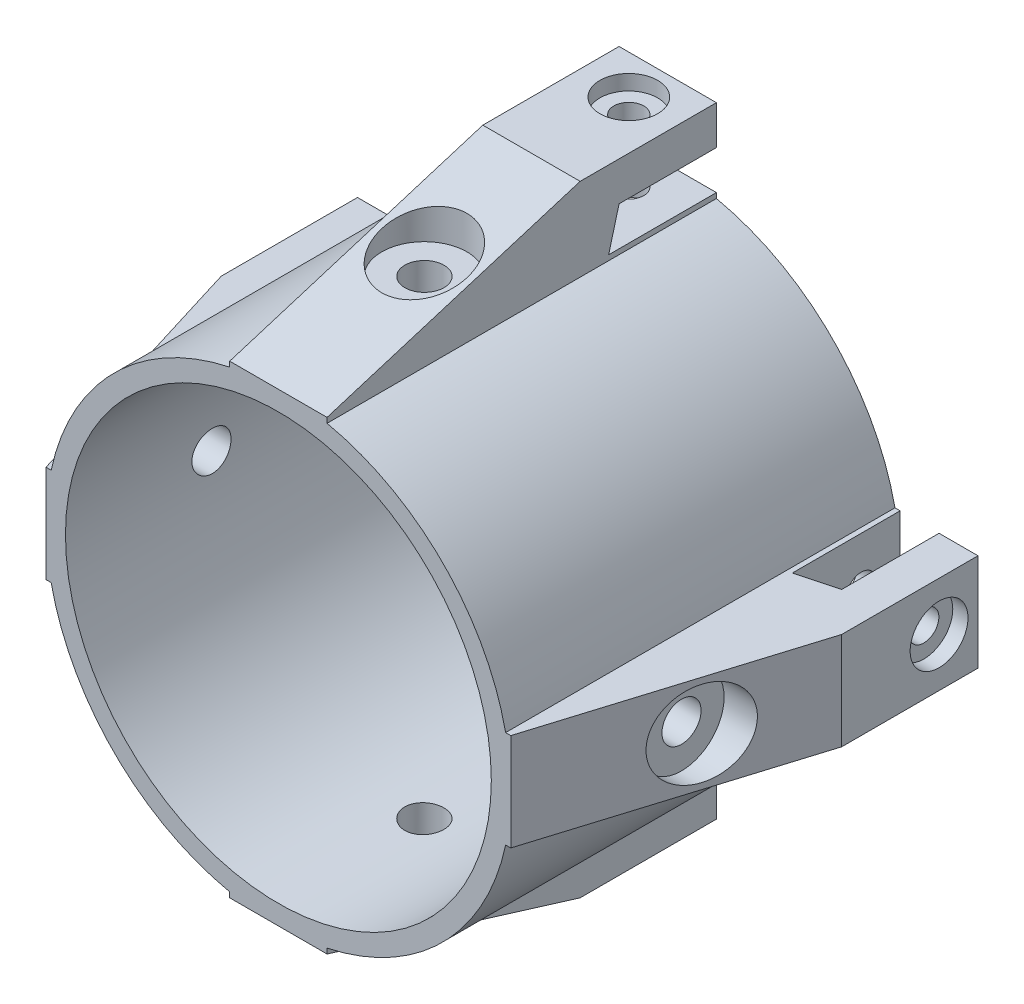
SolidWorks part; units mm, degrees
ref_plane "Front Plane" through (0, 0, 0) normal (1, 0, 0) x (0, 1, 0)
ref_plane "Top Plane" through (0, 0, 0) normal (0, 0, 1) x (0, 1, 0)
ref_plane "Right Plane" through (0, 0, 0) normal (0, 1, 0) x (-1, 0, 0)
sketch "Sketch3" plane through (0, 0, 0) normal (0, 0, 1) x (0, 1, 0)
  circle A0 centre (0, 0) radius 27.7812
  circle A1 centre (0, 0) radius 30.3213
  dimension "D1" = 55.5625
  dimension "D2" = 2.54
extrude "base_ring" add sketch "Sketch3" along normal blind 50.8
sketch "Sketch6" plane through (0, 0, 0) normal (1, 0, 0) x (0, 1, 0)
  line L0 (27.7812, 50.8) -> (27.7812, 0)
  line L1 (-30.3213, 0) -> (30.3213, 0) construction
  line L2 (27.7812, 50.8) -> (30.3213, 50.8)
  line L3 (30.3213, 50.8) -> (40.4813, 17.78)
  line L4 (40.4813, 17.78) -> (40.4813, 0)
  line L5 (40.4813, 0) -> (35.4013, 0)
  line L6 (35.4013, 0) -> (35.4013, 12.7)
  line L7 (35.4013, 12.7) -> (30.3213, 14.0612)
  line L8 (30.3213, 0) -> (30.3213, 50.8) construction
  line L9 (30.3213, 14.0612) -> (30.3213, 0)
  line L10 (30.3213, 0) -> (27.7812, 0)
  point P5 (40.4813, 12.6915)
  dimension "D1" = 75
  dimension "D2" = 5.08
  dimension "D3" = 12.7
  dimension "D4" = 17.78
  dimension "D5" = 5.08
extrude "hook" add sketch "Sketch6" along normal mid plane 12.7
sketch "Sketch7" plane through (0, 40.4813, 0) normal (0, 1, 0) x (-1, 0, 0)
  line L0 (0, 0) -> (0, 5.08) construction
  point P3 (0, 5.08)
  dimension "D2" = 5.08
hole_wizard "CBORE for #5 Binding Head Machine Screw1" positions "Sketch7" profile "Sketch8" counterbore size "#5" standard "ANSI Inch"
sketch "Sketch8" plane through (0, 40.4813, 5.08) normal (1, 0, 0) x (0, 0, 1)
  line L0 (0, 0) -> (0, 39.2752)
  line L1 (0, 39.2752) -> (1.9558, 38.1)
  line L2 (1.9558, 38.1) -> (1.9558, 1.9812)
  line L3 (1.9558, 1.9812) -> (3.7706, 1.9812)
  line L4 (3.7706, 1.9812) -> (3.7706, 0)
  line L5 (3.7706, 0) -> (0, 0)
  line L10 (0, 39.2752) -> (-1.9558, 38.1) construction
  line L11 (0, -6.35) -> (0, 107.95) construction
  dimension "Hole Dia." = 3.9116
  dimension "Hole Depth" = 38.1
  dimension "C'Bore Dia." = 7.5413
  dimension "C'Bore Depth" = 1.9812
  dimension "Drill Angle" = 118
sketch "Sketch9" plane through (0, 40.4813, 0) normal (0, 1, 0) x (-1, 0, 0)
  line L0 (0, 0) -> (0, 31.75) construction
  point P4 (0, 31.75)
  dimension "D1" = 31.75
hole_wizard "CBORE for #10 Binding Head Machine Screw2" positions "Sketch9" profile "Sketch10" counterbore size "#10" standard "ANSI Inch"
sketch "Sketch10" plane through (0, 40.4813, 31.75) normal (1, 0, 0) x (0, 0, 1)
  line L0 (0, 0) -> (0, 39.6338)
  line L1 (0, 39.6338) -> (2.5527, 38.1)
  line L2 (2.5527, 38.1) -> (2.5527, 6.9342)
  line L3 (2.5527, 6.9342) -> (5.5562, 6.9342)
  line L4 (5.5562, 6.9342) -> (5.5562, 0)
  line L5 (5.5562, 0) -> (0, 0)
  line L10 (0, 39.6338) -> (-2.5527, 38.1) construction
  line L11 (0, -6.35) -> (0, 107.95) construction
  dimension "Hole Dia." = 5.1054
  dimension "Hole Depth" = 38.1
  dimension "C'Bore Dia." = 11.1125
  dimension "C'Bore Depth" = 6.9342
  dimension "Drill Angle" = 118
pattern_circular "CirPattern1" count 4 over 360 about axis through (0, 0, 0) along (0, 0, 1) of "hook", "CBORE for #5 Binding Head Machine Screw1", "CBORE for #10 Binding Head Machine Screw2"
